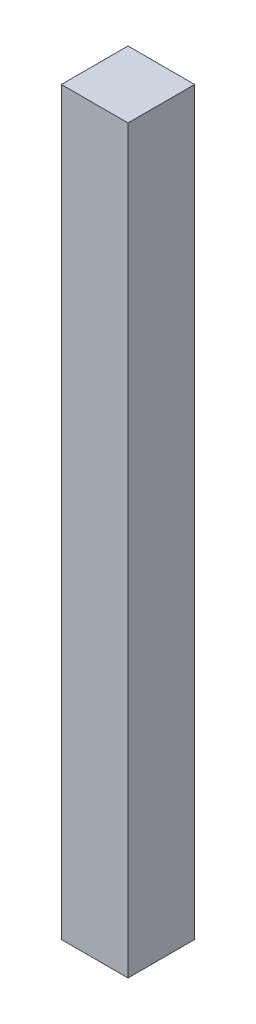
SolidWorks part; units mm, degrees
ref_plane "Front Plane" through (0, 0, 0) normal (0, 0, 1) x (1, 0, 0)
ref_plane "Top Plane" through (0, 0, 0) normal (0, 1, 0) x (1, 0, 0)
ref_plane "Right Plane" through (0, 0, 0) normal (1, 0, 0) x (0, 0, -1)
other "Configuration Table"
sketch "Sketch1" plane through (0, 0, 0) normal (0, 0, 1) x (1, 0, 0)
  line L1 (45, 1180) -> (63, 1180)
  line L2 (45, 1180) -> (45, 1380)
  line L3 (45, 1380) -> (63, 1380)
  line L4 (63, 1180) -> (63, 1380)
extrude "TOPPING_klape_kat2_gazli_amortisor_1_1" add sketch "Sketch1" along normal blind 18 from offset 8 separate body
